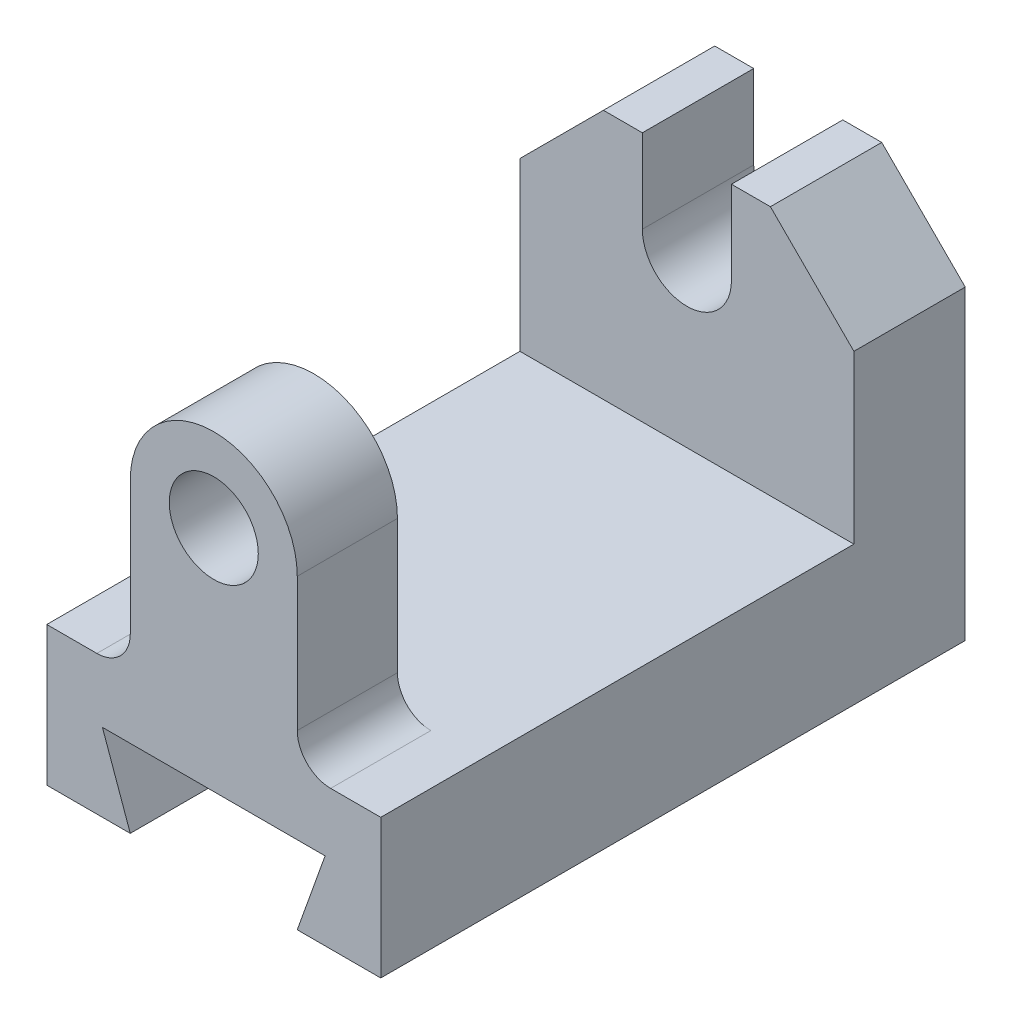
SolidWorks part; units mm, degrees
ref_plane "Front Plane" through (0, 0, 0) normal (0, 0, 1) x (1, 0, 0)
ref_plane "Top Plane" through (0, 0, 0) normal (0, 1, 0) x (1, 0, 0)
ref_plane "Right Plane" through (0, 0, 0) normal (1, 0, 0) x (0, 0, -1)
sketch "Sketch1" plane through (0, 0, 0) normal (0, 0, 1) x (1, 0, 0)
  line L0 (45, 0) -> (60, 0)
  line L1 (0, 0) -> (15, 0)
  line L2 (0, 0) -> (0, 25)
  line L3 (0, 25) -> (60, 25)
  line L4 (60, 0) -> (60, 25)
  line L5 (10, 14) -> (50, 14)
  line L10 (15, 0) -> (10, 14)
  line L11 (50, 14) -> (45, 0)
  line L13 (15, 0) -> (45, 0) construction
  point P6 (30, 0)
  point P9 (30, 25)
  point P10 (30, 14)
  dimension "D1" = 60
  dimension "D2" = 25
  dimension "D3" = 14
  dimension "D4" = 40
  dimension "D5" = 30
extrude "Boss-Extrude1" add sketch "Sketch1" against normal blind 105
sketch "Sketch2" plane through (0, 0, 0) normal (0, 0, 1) x (1, 0, 0)
  line L2 (15, 55) -> (15, 25)
  line L3 (15, 25) -> (45, 25)
  line L4 (45, 55) -> (45, 25)
  line L6 (60, 25) -> (0, 25) construction
  line L7 (0, 0) -> (15, 0) construction
  circle A0 centre (30, 55) radius 8
  arc A1 (45, 55) -> (15, 55) centre (30, 55) ccw
  point P2 (0, 0)
  point P9 (44.7713, 55.8091)
  point P10 (45, 57.4634)
  point P11 (30, 25)
  point P12 (15, 58.0107)
  dimension "D1" = 30
  dimension "D2" = 16
  dimension "D3" = 55
  dimension "D4" = 30
extrude "Boss-Extrude2" add sketch "Sketch2" against normal blind 18
fillet "Fillet1" radius 6 2 edges at (15, 25, -9) (45, 25, -9)
sketch "Sketch3" plane through (0, 0, -105) normal (0, 0, -1) x (-1, 0, 0)
  line L0 (-60, 55) -> (-45, 70)
  line L1 (-60, 25) -> (0, 25)
  line L2 (-60, 25) -> (-60, 55)
  line L3 (-45, 70) -> (-38, 70)
  line L4 (0, 25) -> (0, 55)
  line L5 (-15, 70) -> (0, 55)
  line L6 (-38, 55) -> (-38, 70)
  line L7 (-22, 70) -> (-15, 70)
  line L8 (-22, 55) -> (-22, 70)
  arc A0 (-38, 55) -> (-22, 55) centre (-30, 55) ccw
  point P1 (0, 70)
  point P2 (-60, 70)
  point P10 (0, 0)
  point P13 (0, 0)
  point P16 (0, 0)
  point P17 (-30, 25)
  point P18 (-25.4069, 50.0567)
  point P20 (-22, 65.8298)
  dimension "D6" = 16
  dimension "D1" = 15
  dimension "D2" = 45
  dimension "D3" = 15
  dimension "D4" = 45
  dimension "D5" = 30
  dimension "D7" = 45
extrude "Boss-Extrude3" add sketch "Sketch3" against normal blind 20
